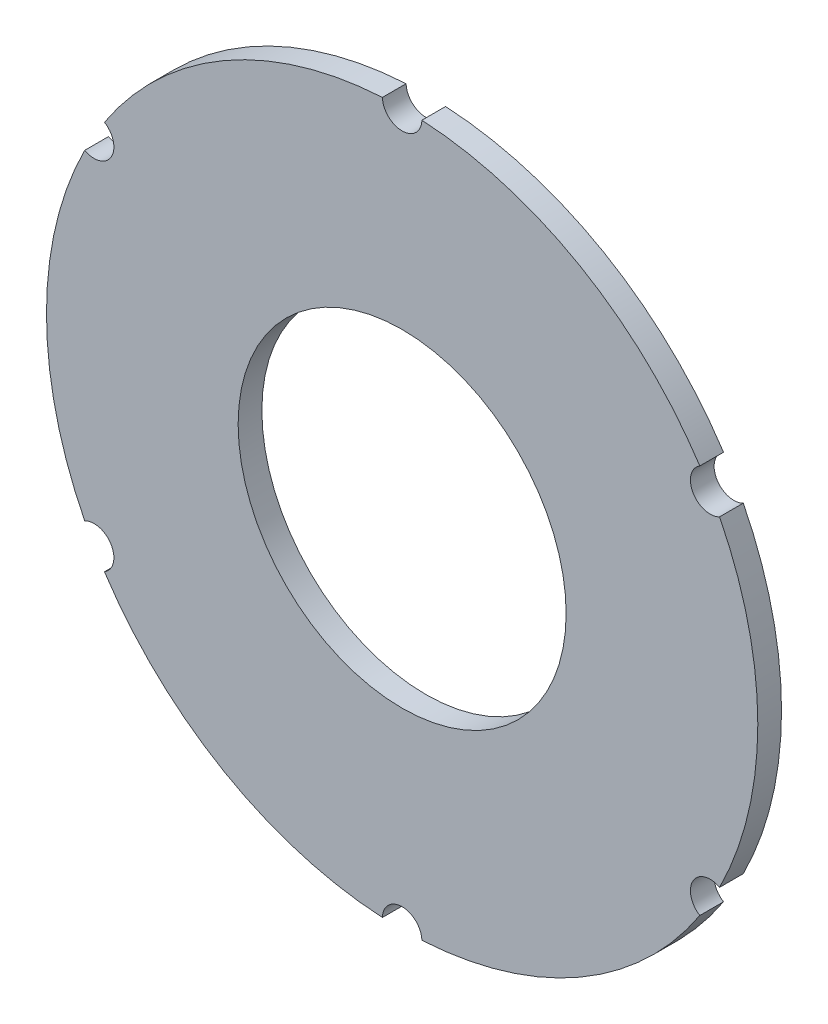
SolidWorks part; units mm, degrees
ref_plane "Front Plane" through (0, 0, 0) normal (0, 0, 1) x (1, 0, 0)
ref_plane "Top Plane" through (0, 0, 0) normal (0, 1, 0) x (1, 0, 0)
ref_plane "Right Plane" through (0, 0, 0) normal (1, 0, 0) x (0, 0, -1)
sketch "Sketch1" plane through (0, 0, 0) normal (0, 0, 1) x (1, 0, 0)
  circle A0 centre (0, 0) radius 90
  circle A1 centre (0, 0) radius 41.5
  dimension "D1" = 180
  dimension "D2" = 83
extrude "Boss-Extrude1" add sketch "Sketch1" along normal blind 6
sketch "Sketch2" plane through (0, 0, 0) normal (0, 0, 1) x (1, 0, 0)
  line L0 (0, 0) -> (0, 90) construction
  line L1 (0, 0) -> (77.9423, 45) construction
  line L2 (0, 0) -> (77.9423, -45) construction
  line L3 (0, 0) -> (0, -90) construction
  circle A1 centre (0, 0) radius 90 construction
  circle A3 centre (0, 0) radius 90 construction
  point P1 (0, 90)
  point P3 (77.9423, 45)
  point P4 (-77.9423, 45)
  point P6 (-77.9423, -45)
  point P10 (77.9423, -45)
  point P17 (0, -90)
  point P18 (69.282, 40)
  point P22 (69.282, -40)
  dimension "D1" = 60
  dimension "D3" = 60
hole_wizard "Ø10.0mm Dowel Hole1" positions "Sketch3" profile "Sketch4" hole size "Ø10.0" standard "ISO"
sketch "Sketch3" plane through (0, 0, 0) normal (0, 0, -1) x (-1, 0, 0)
  point P24 (-77.9423, 45)
  point P27 (-77.9423, -45)
  point P30 (0, -90)
  point P33 (77.9423, -45)
  point P36 (77.9423, 45)
  point P39 (0, 90)
sketch "Sketch4" plane through (77.9423, 45, 0) normal (1, 0, 0) x (0, 1, 0)
  line L0 (0, 0) -> (0, 12.9103)
  line L1 (0, 12.9103) -> (5, 9.906)
  line L2 (5, 9.906) -> (5, 0)
  line L5 (5, 0) -> (0, 0)
  line L10 (0, 12.9103) -> (-5, 9.906) construction
  line L11 (0, -6.35) -> (0, 107.95) construction
  dimension "Hole Dia." = 10
  dimension "Hole Depth" = 9.906
  dimension "Drill Angle" = 118
